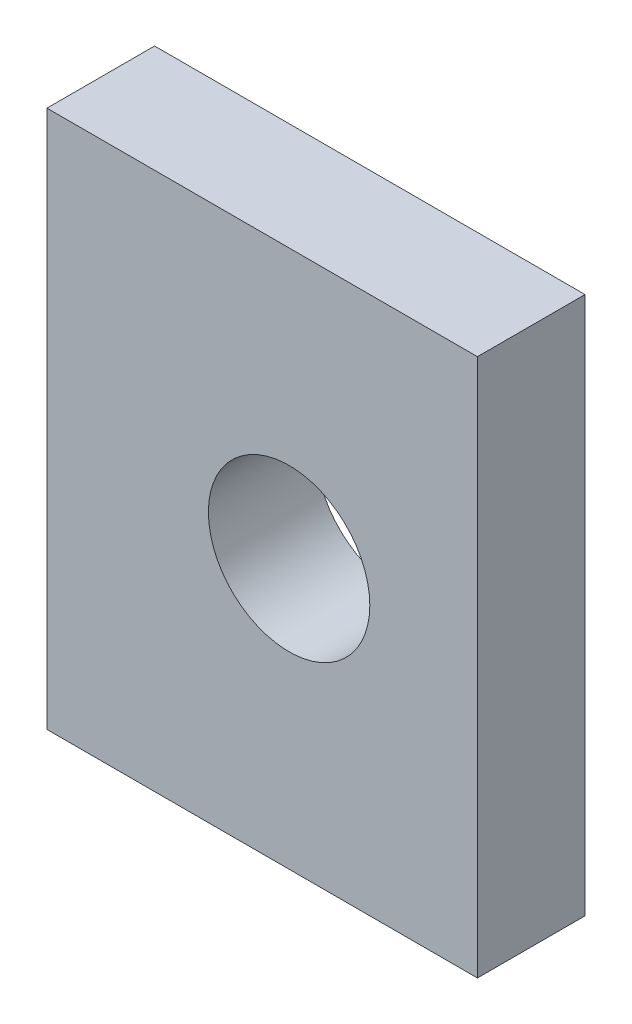
SolidWorks part; units mm, degrees
ref_plane "Front Plane" through (0, 0, 0) normal (0, 0, 1) x (1, 0, 0)
ref_plane "Top Plane" through (0, 0, 0) normal (0, 1, 0) x (1, 0, 0)
ref_plane "Right Plane" through (0, 0, 0) normal (1, 0, 0) x (0, 0, -1)
sketch "Sketch1" plane through (0, 0, 0) normal (0, 0, 1) x (1, 0, 0)
  line L0 (0, 10) -> (8, 10)
  line L1 (8, 0) -> (0, 0)
  line L2 (0, 10) -> (0, 0)
  line L3 (8, 10) -> (8, 0)
  circle A0 centre (4.5, 5) radius 1.5
  dimension "D1" = 10
  dimension "D2" = 8
extrude "Boss-Extrude1" add sketch "Sketch1" along normal blind 2
